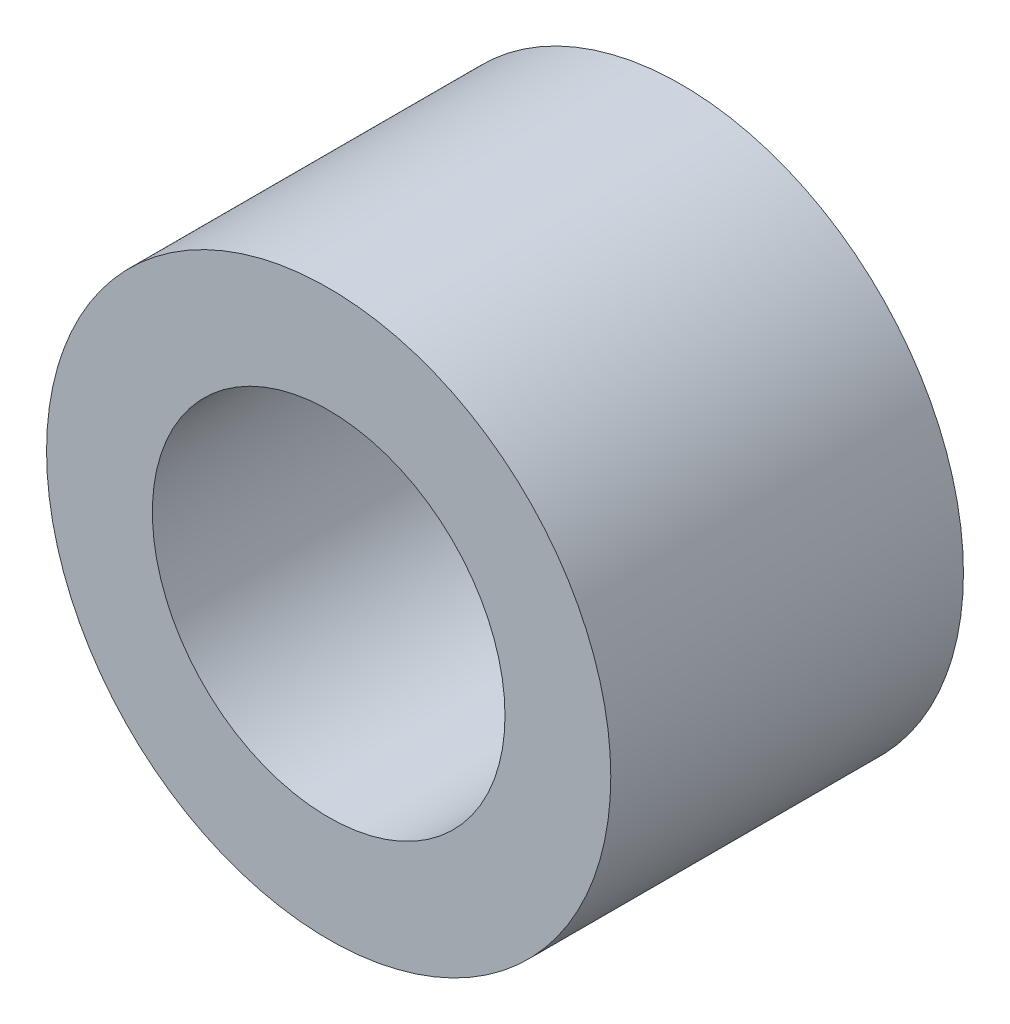
SolidWorks part; units mm, degrees
ref_plane "Plan de face" through (0, 0, 0) normal (0, 0, 1) x (1, 0, 0)
ref_plane "Plan de dessus" through (0, 0, 0) normal (0, 1, 0) x (1, 0, 0)
ref_plane "Plan de droite" through (0, 0, 0) normal (1, 0, 0) x (0, 0, -1)
sketch "Esquisse1" plane through (0, 0, 0) normal (0, 0, 1) x (1, 0, 0)
  circle A0 centre (0, 0) radius 4
  circle A1 centre (0, 0) radius 2.5
extrude "Boss.-Extru.1" add sketch "Esquisse1" along normal blind 5
